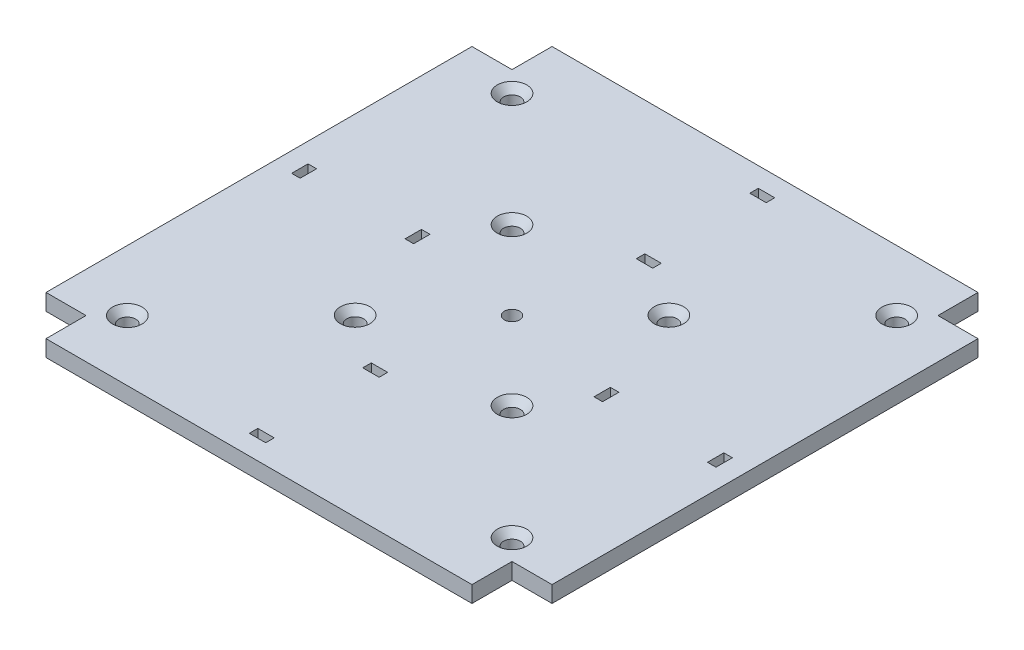
SolidWorks part; units mm, degrees
material "ABS"
ref_plane "Front Plane" through (0, 0, 0) normal (0, 0, 1) x (1, 0, 0)
ref_plane "Top Plane" through (0, 0, 0) normal (0, 1, 0) x (1, 0, 0)
ref_plane "Right Plane" through (0, 0, 0) normal (1, 0, 0) x (0, 0, -1)
sketch "Sketch1" plane through (0, 0, 0) normal (0, 1, 0) x (1, 0, 0)
  line L1 (-49, -49) -> (49, -49)
  line L2 (-49, -49) -> (-49, 49)
  line L3 (-49, 49) -> (49, 49)
  line L4 (49, -49) -> (49, 49)
  line L5 (-49, -49) -> (49, 49) construction
  line L6 (-49, 49) -> (49, -49) construction
  point P0 (0, 0)
  dimension "D1" = 98
extrude "Boss-Extrude1" add sketch "Sketch1" along normal blind 3.175
sketch "Sketch2" plane through (0, 3.175, 0) normal (0, 1, 0) x (1, 0, 0)
  line L0 (41.5, 49) -> (49, 49)
  line L1 (-49, 49) -> (-41.5, 49)
  line L2 (-49, 49) -> (-49, 41.5)
  line L3 (-49, 41.5) -> (-41.5, 41.5)
  line L4 (-41.5, 49) -> (-41.5, 41.5)
  line L5 (41.5, 49) -> (41.5, 41.5)
  line L6 (41.5, 41.5) -> (49, 41.5)
  line L7 (49, 49) -> (49, 41.5)
  line L8 (41.5, -41.5) -> (49, -41.5)
  line L9 (41.5, -41.5) -> (41.5, -49)
  line L10 (41.5, -49) -> (49, -49)
  line L11 (49, -41.5) -> (49, -49)
  line L12 (-49, -41.5) -> (-41.5, -41.5)
  line L13 (-49, -41.5) -> (-49, -49)
  line L14 (-49, -49) -> (-41.5, -49)
  line L15 (-41.5, -41.5) -> (-41.5, -49)
  line L16 (49, -49) -> (49, 49) construction
  line L17 (-49, -49) -> (49, -49) construction
  line L18 (49, 49) -> (-49, 49) construction
  dimension "D1" = 7.5
  dimension "D2" = 2
  dimension "D3" = 2
extrude "Cut-Extrude1" cut sketch "Sketch2" against normal through all
hole_wizard "#4 Clearance Hole1" positions "Sketch5" profile "Sketch4" hole size "#4" standard "ANSI Inch" end condition through all
sketch "Sketch5" plane through (0, 3.175, 0) normal (0, 1, 0) x (1, 0, 0)
  point P0 (0, 0)
sketch "Sketch4" plane through (0, 3.175, 0) normal (1, 0, 0) x (0, 0, 1)
  line L0 (0, 0) -> (0, 3.175)
  line L1 (0, 3.175) -> (1.4732, 3.175)
  line L2 (1.4732, 3.175) -> (1.4732, 0)
  line L5 (1.4732, 0) -> (0, 0)
  line L11 (0, -6.35) -> (0, 107.95) construction
  dimension "Thru Hole Dia." = 2.9464
  dimension "Thru Hole Depth" = 3.175
hole_wizard "CSK for #4 Flat Head Machine Screw1" positions "Sketch10" profile "Sketch9" countersink size "#4" standard "ANSI Inch" end condition through all
sketch "Sketch10" plane through (0, 3.175, 0) normal (0, 1, 0) x (1, 0, 0)
  circle A0 centre (37.25, -37.25) radius 1.4732 construction
  circle A1 centre (37.25, 37.25) radius 1.4732 construction
  circle A2 centre (-37.25, 37.25) radius 1.4732 construction
  circle A3 centre (-37.25, -37.25) radius 1.4732 construction
  point P0 (37.25, -37.25)
  point P2 (-37.25, -37.25)
  point P4 (-37.25, 37.25)
  point P6 (37.25, 37.25)
sketch "Sketch9" plane through (37.25, 3.175, 37.25) normal (1, 0, 0) x (0, 0, 1)
  line L0 (0, 0) -> (0, 3.175)
  line L1 (0, 3.175) -> (1.6319, 3.175)
  line L2 (1.6319, 3.175) -> (1.6319, 1.4098)
  line L3 (1.6319, 1.4098) -> (2.8575, 0)
  line L5 (2.8575, 0) -> (0, 0)
  line L6 (-1.6319, 1.4098) -> (-2.8575, 0) construction
  line L11 (0, -6.35) -> (0, 107.95) construction
  dimension "Thru Hole Dia." = 3.2639
  dimension "Thru Hole Depth" = 3.175
  dimension "Near C'Sink Dia." = 5.715
  dimension "Near C'Sink Angle" = 82
hole_wizard "CSK for #4 Flat Head Machine Screw2" positions "Sketch14" profile "Sketch13" countersink size "#4" standard "ANSI Inch" end condition through all
sketch "Sketch14" plane through (0, 3.175, 0) normal (0, 1, 0) x (1, 0, 0)
  line L1 (15.1384, 15.24) -> (-15.24, 15.24) construction
  line L2 (15.1384, 15.24) -> (15.1384, -15.1384) construction
  line L3 (15.1384, -15.1384) -> (-15.24, -15.1384) construction
  line L4 (-15.24, 15.24) -> (-15.24, -15.1384) construction
  line L6 (41.5, 49) -> (-41.5, 49) construction
  line L7 (-49, 41.5) -> (-49, -41.5) construction
  point P0 (15.1384, 15.24)
  point P2 (-15.24, 15.24)
  point P4 (-15.24, -15.1384)
  point P6 (15.1384, -15.1384)
  dimension "D1" = 30.3784
  dimension "D2" = 33.76
  dimension "D3" = 33.76
sketch "Sketch13" plane through (15.1384, 3.175, -15.24) normal (1, 0, 0) x (0, 0, 1)
  line L0 (0, 0) -> (0, 3.175)
  line L1 (0, 3.175) -> (1.6319, 3.175)
  line L2 (1.6319, 3.175) -> (1.6319, 1.4098)
  line L3 (1.6319, 1.4098) -> (2.8575, 0)
  line L5 (2.8575, 0) -> (0, 0)
  line L6 (-1.632, 1.4098) -> (-2.8575, 0) construction
  line L11 (0, -6.35) -> (0, 107.95) construction
  dimension "Thru Hole Dia." = 3.2639
  dimension "Thru Hole Depth" = 3.175
  dimension "Near C'Sink Dia." = 5.715
  dimension "Near C'Sink Angle" = 82
sketch "Sketch15" plane through (0, 3.175, 0) normal (0, 1, 0) x (1, 0, 0)
  line L1 (-48.746, -41.246) -> (-41.246, -41.246)
  line L2 (-41.246, -41.246) -> (-41.246, -48.746)
  line L3 (49, 41.246) -> (49, 41.5)
  line L4 (41.246, -48.746) -> (41.246, -41.246)
  line L5 (41.246, -41.246) -> (48.746, -41.246)
  line L7 (48.746, 41.246) -> (41.246, 41.246)
  line L8 (41.246, 41.246) -> (41.246, 48.746)
  line L9 (49, -41.5) -> (49, 41.5) construction
  line L10 (-41.246, 48.746) -> (-41.246, 41.246)
  line L11 (-41.246, 41.246) -> (-48.746, 41.246)
  line L12 (-49, 41.5) -> (-49, -41.5)
  line L13 (-49, -41.5) -> (-41.5, -41.5)
  line L14 (-41.5, -41.5) -> (-41.5, -49)
  line L15 (-41.5, -49) -> (41.5, -49)
  line L16 (41.5, -49) -> (41.5, -41.5)
  line L17 (41.5, -41.5) -> (49, -41.5)
  line L18 (49, -41.5) -> (49, 41.5)
  line L19 (49, 41.5) -> (41.5, 41.5)
  line L20 (41.5, 41.5) -> (41.5, 49)
  line L21 (41.5, 49) -> (-41.5, 49)
  line L22 (-41.5, 49) -> (-41.5, 41.5)
  line L23 (-41.5, 41.5) -> (-49, 41.5)
  line L24 (-49, 41.5) -> (-49, 41.246)
  line L25 (-49, -41.5) -> (-41.5, -41.5)
  line L26 (-41.5, -41.5) -> (-41.5, -49)
  line L27 (-41.5, -49) -> (-41.246, -49)
  line L28 (41.5, -49) -> (41.5, -41.5)
  line L29 (41.5, -41.5) -> (49, -41.5)
  line L30 (49, -41.5) -> (49, -41.246)
  line L31 (49, 41.5) -> (41.5, 41.5)
  line L32 (41.5, 41.5) -> (41.5, 49)
  line L33 (41.5, 49) -> (41.246, 49)
  line L34 (-41.5, 49) -> (-41.5, 41.5)
  line L35 (-41.5, 41.5) -> (-49, 41.5)
  line L36 (-48.746, 41.246) -> (-49, 41.246)
  line L37 (-48.746, -41.246) -> (-49, -41.246)
  line L38 (-41.246, -48.746) -> (-41.246, -49)
  line L39 (41.246, -48.746) -> (41.246, -49)
  line L40 (48.746, -41.246) -> (49, -41.246)
  line L41 (48.746, 41.246) -> (49, 41.246)
  line L42 (41.246, 48.746) -> (41.246, 49)
  line L43 (-41.246, 48.746) -> (-41.246, 49)
  line L44 (-41.246, 49) -> (-41.5, 49)
  line L45 (41.5, 49) -> (-41.5, 49) construction
  line L46 (41.246, -49) -> (41.5, -49)
  line L47 (-41.5, -49) -> (41.5, -49) construction
  line L48 (41.246, 48.746) -> (-41.246, 48.746) construction
  line L49 (-41.246, -48.746) -> (41.246, -48.746) construction
  line L50 (48.746, -41.246) -> (48.746, 41.246) construction
  line L51 (-48.746, 41.246) -> (-48.746, -41.246) construction
  line L52 (-49, -41.246) -> (-49, -41.5)
  line L53 (-49, 41.5) -> (-49, -41.5) construction
  dimension "D1" = 0
  dimension "D2" = 0.254
extrude "Cut-Extrude2" cut sketch "Sketch15" against normal through all
sketch "Sketch16" plane through (0, 0, 0) normal (0, -1, 0) x (1, 0, 0)
  line L0 (-49, -41.246) -> (-49, 41.246) construction
  line L1 (-45.19, -5.686) -> (-43.539, -5.686)
  line L2 (-45.19, -5.686) -> (-45.19, -2.511)
  line L3 (-45.19, -2.511) -> (-43.539, -2.511)
  line L4 (-43.539, -5.686) -> (-43.539, -2.511)
  line L5 (-23.219, -5.686) -> (-21.568, -5.686)
  line L6 (-23.219, -5.686) -> (-23.219, -2.511)
  line L7 (-23.219, -2.511) -> (-21.568, -2.511)
  line L8 (-21.568, -5.686) -> (-21.568, -2.511)
  line L9 (-49, -41.246) -> (-41.246, -41.246) construction
  dimension "D1" = 1.651
  dimension "D2" = 3.175
  dimension "D3" = 20.32
  dimension "D4" = 3.81
  dimension "D5" = 35.56
extrude "Cut-Extrude3" cut sketch "Sketch16" against normal through all
pattern_circular "CirPattern1" count 4 over 360 about axis through (0, 0, 0) along (0, 1, 0) of "Cut-Extrude3"
